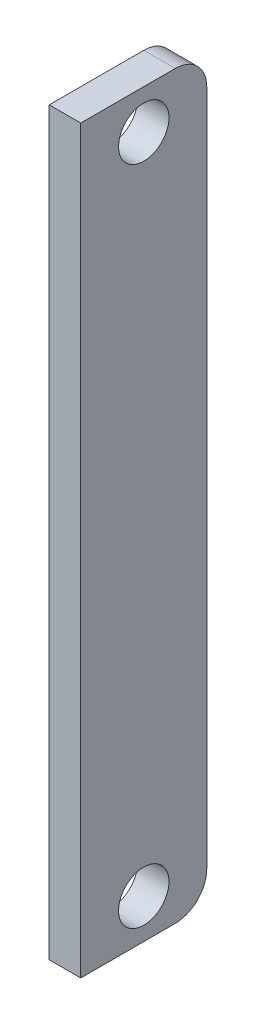
SolidWorks part; units mm, degrees
material "Kiefer"
ref_plane "Ebene vorne" through (0, 0, 0) normal (0, 0, 1) x (1, 0, 0)
ref_plane "Ebene oben" through (0, 0, 0) normal (0, 1, 0) x (1, 0, 0)
ref_plane "Ebene rechts" through (0, 0, 0) normal (1, 0, 0) x (0, 0, -1)
sketch "Skizze1" plane through (0, 0, 0) normal (1, 0, 0) x (0, 0, -1)
  line L1 (-20, 117.5) -> (20, 117.5)
  line L2 (-20, 117.5) -> (-20, -117.5)
  line L3 (-20, -117.5) -> (20, -117.5)
  line L4 (20, 117.5) -> (20, -117.5)
  line L5 (-20, 117.5) -> (20, -117.5) construction
  line L6 (-20, -117.5) -> (20, 117.5) construction
  point P0 (0, 0)
  dimension "D1" = 235
  dimension "D2" = 40
extrude "Aufsatz-Linear austragen1" add sketch "Skizze1" along normal blind 10
sketch "Skizze2" plane through (10, 0, 0) normal (1, 0, 0) x (0, 0, -1)
  line L0 (0, 117.5) -> (0, -117.5) construction
  line L1 (20, 117.5) -> (-20, 117.5) construction
  line L2 (-20, -117.5) -> (20, -117.5) construction
  circle A0 centre (0, 105) radius 8
  circle A1 centre (0, -105) radius 8
  dimension "D1" = 16
  dimension "D2" = 16
  dimension "D3" = 210
  dimension "D4" = 12.5
extrude "Schnitt-Linear austragen1" cut sketch "Skizze2" against normal through all
fillet "Verrundung1" radius 10 2 edges at (5, -117.5, -20) (5, 117.5, -20)
